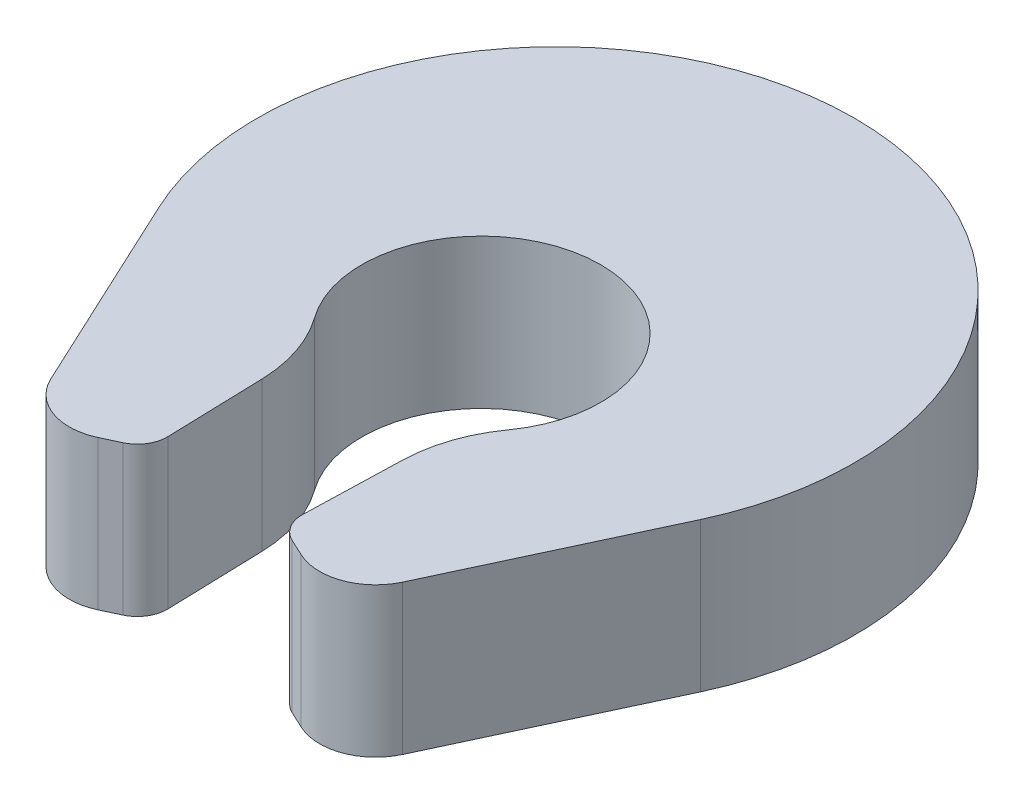
SolidWorks part; units mm, degrees
ref_plane "Front Plane" through (0, 0, 0) normal (0, 0, 1) x (1, 0, 0)
ref_plane "Top Plane" through (0, 0, 0) normal (0, 1, 0) x (1, 0, 0)
ref_plane "Right Plane" through (0, 0, 0) normal (1, 0, 0) x (0, 0, -1)
sketch "Sketch2" plane through (0, 0, 0) normal (0, 1, 0) x (1, 0, 0)
  line L0 (-3.6252, -1.6905) -> (-2.3574, -4.4094)
  line L1 (3.6252, -1.6905) -> (2.3574, -4.4094)
  line L2 (0, 0) -> (0, 13.3326) construction
  line L5 (-0.9417, -2.9927) -> (-0.9033, -4.2922)
  line L6 (0.9417, -2.9927) -> (0.9033, -4.2922)
  line L7 (-2.3574, -4.4094) -> (-0.0898, -3.352) construction
  line L8 (-1.1341, -4.6665) -> (-1.3607, -4.7722)
  line L10 (1.1341, -4.6665) -> (1.3607, -4.7722)
  line L11 (2.3574, -4.4094) -> (0.2286, -3.4167) construction
  arc A0 (-3.6252, -1.6905) -> (3.6252, -1.6905) centre (0, 0) cw
  arc A4 (-1.3, -1.9327) -> (1.3, -1.9327) centre (0, -1) cw
  arc A5 (-1.3, -1.9327) -> (-0.9417, -2.9927) centre (-2.8562, -3.0493) cw
  arc A6 (1.3, -1.9327) -> (0.9417, -2.9927) centre (2.8562, -3.0493) ccw
  arc A8 (-0.9033, -4.2922) -> (-1.1341, -4.6665) centre (-1.3032, -4.304) cw
  arc A9 (-1.3607, -4.7722) -> (-2.3574, -4.4094) centre (-1.6776, -4.0924) cw
  arc A11 (1.3607, -4.7722) -> (2.3574, -4.4094) centre (1.6776, -4.0924) ccw
  arc A12 (1.1341, -4.6665) -> (0.9033, -4.2922) centre (1.3032, -4.304) cw
  point P16 (-0.9194, -1.8217)
  dimension "D1" = 25
  dimension "D3" = 4
  dimension "D4" = 1
  dimension "D5" = 1.6
  dimension "D6" = 2.6
  dimension "D10" = 0.4
  dimension "D2" = 3
  dimension "D7" = 1.3
  dimension "D8" = 0.25
  dimension "D9" = 0.75
extrude "Boss-Extrude1" add sketch "Sketch2" along normal blind 2
